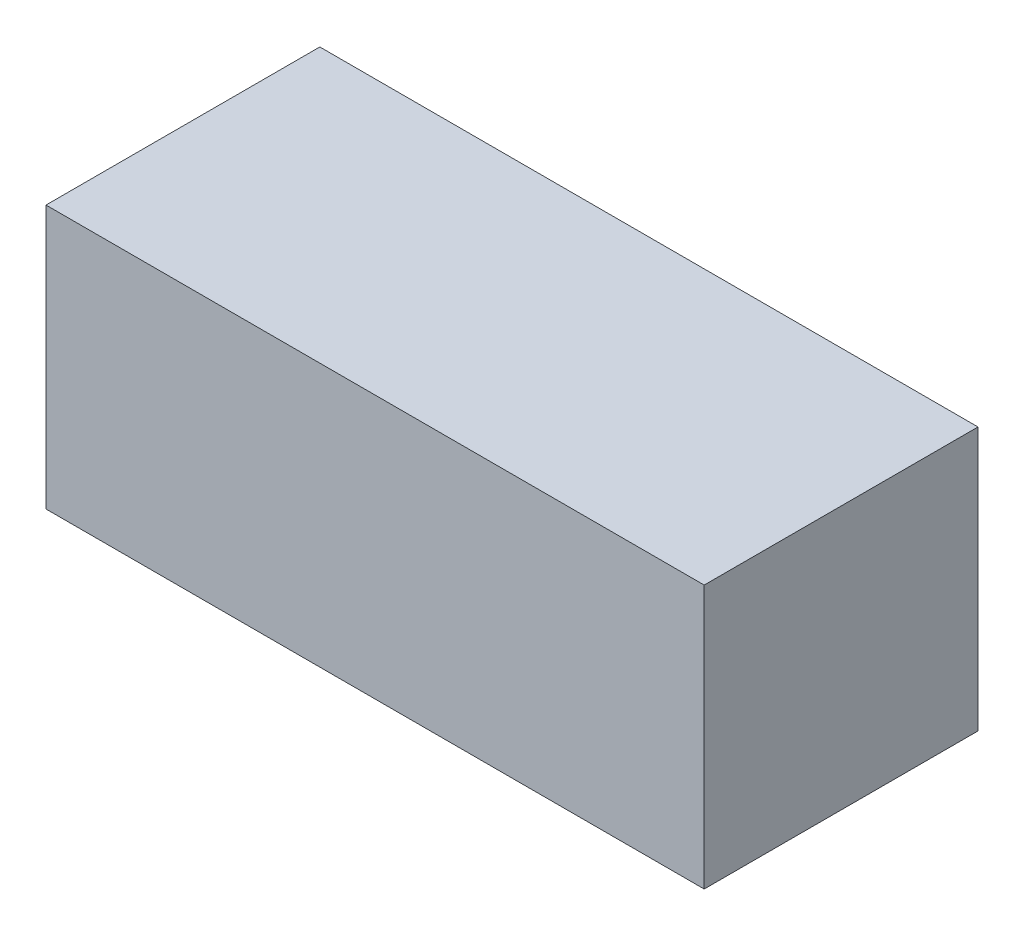
SolidWorks part; units mm, degrees
ref_plane "Ebene vorne" through (0, 0, 0) normal (0, 0, 1) x (1, 0, 0)
ref_plane "Ebene oben" through (0, 0, 0) normal (0, 1, 0) x (1, 0, 0)
ref_plane "Ebene rechts" through (0, 0, 0) normal (1, 0, 0) x (0, 0, -1)
sketch "Skizze1" plane through (0, 0, 0) normal (0, 0, 1) x (1, 0, 0)
  line L0 (0, 0) -> (0, 400)
  line L1 (0, 400) -> (1000, 400)
  line L2 (1000, 400) -> (1000, 0)
  line L3 (16, 0) -> (16, 384)
  line L4 (16, 384) -> (984, 384)
  line L5 (984, 384) -> (984, 0)
  line L6 (0, 0) -> (16, 0)
  line L7 (1000, 0) -> (984, 0)
  point P3 (1000, 789.2752)
  point P6 (1000, 44.7085)
  dimension "D1" = 1000
  dimension "D2" = 400
  dimension "D3" = 16
extrude "Aufsatz-Linear austragen1" add sketch "Skizze1" against normal blind 400
sketch "Skizze2" plane through (0, 0, 0) normal (0, 0, 1) x (1, 0, 0)
  line L1 (0, 400) -> (1000, 400)
  line L2 (0, 400) -> (0, 0)
  line L3 (0, 0) -> (1000, 0)
  line L4 (1000, 400) -> (1000, 0)
extrude "Aufsatz-Linear austragen2" add sketch "Skizze2" along normal blind 16
